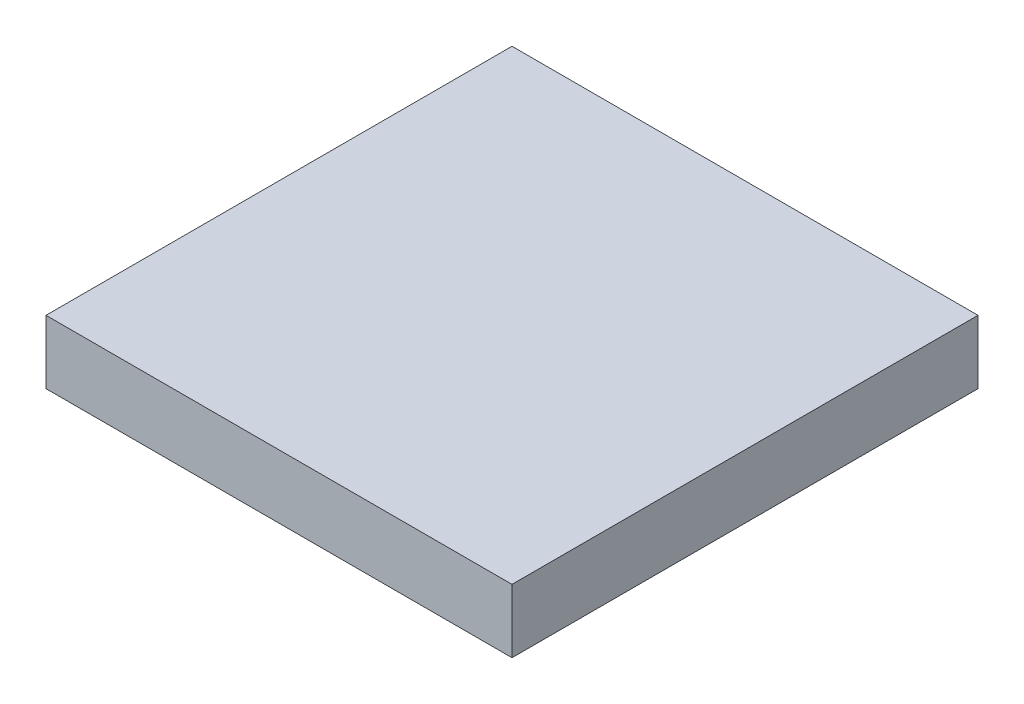
SolidWorks part; units mm, degrees
material "ABS"
ref_plane "Front Plane" through (0, 0, 0) normal (0, 0, 1) x (1, 0, 0)
ref_plane "Top Plane" through (0, 0, 0) normal (0, 1, 0) x (1, 0, 0)
ref_plane "Right Plane" through (0, 0, 0) normal (1, 0, 0) x (0, 0, -1)
sketch "Sketch1" plane through (0, 0, 0) normal (0, 1, 0) x (1, 0, 0)
  line L1 (0, 0) -> (220, 0)
  line L2 (0, 0) -> (0, 220)
  line L3 (0, 220) -> (220, 220)
  line L4 (220, 0) -> (220, 220)
extrude "Boss-Extrude1" add sketch "Sketch1" along normal blind 30
